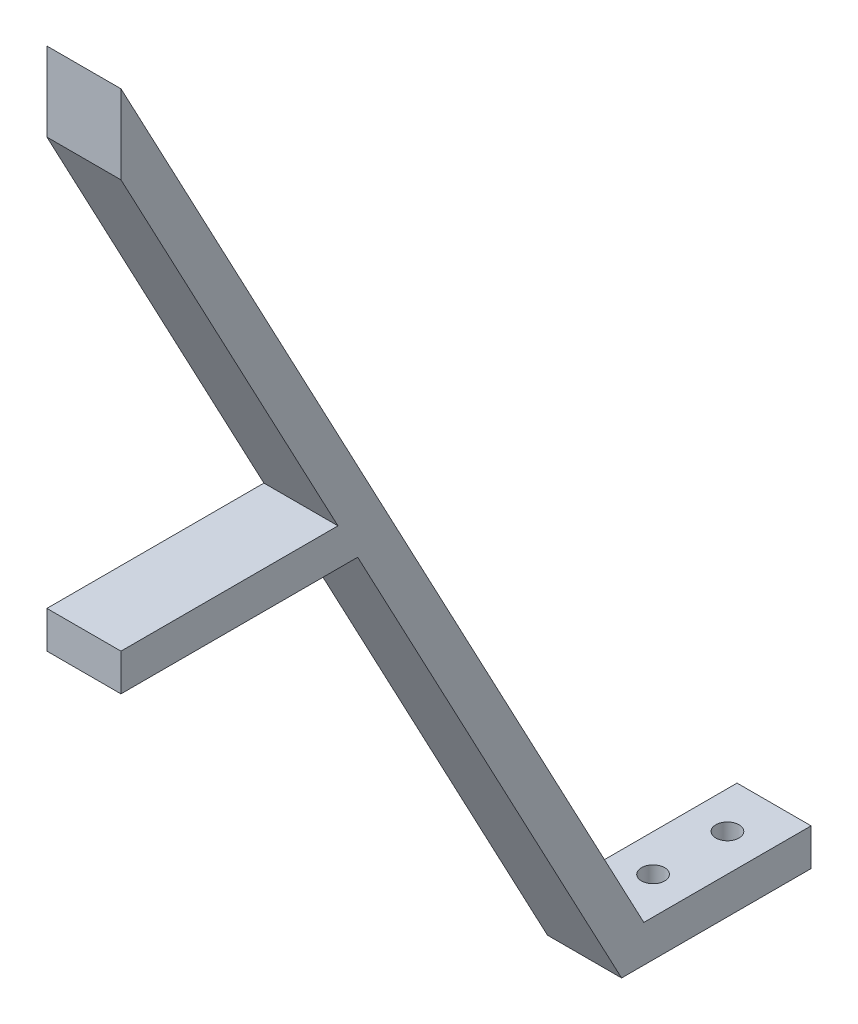
SolidWorks part; units mm, degrees
ref_plane "Alzado" through (0, 0, 0) normal (0, 0, 1) x (1, 0, 0)
ref_plane "Planta" through (0, 0, 0) normal (0, 1, 0) x (1, 0, 0)
ref_plane "Vista lateral" through (0, 0, 0) normal (1, 0, 0) x (0, 0, -1)
sketch "Croquis2" plane through (0, 0, 0) normal (1, 0, 0) x (0, 0, -1)
  line L0 (1.6204, -200.3696) -> (1.6204, 499.6304) construction
  line L1 (1.6204, 499.6304) -> (360.3116, -174.9696)
  line L2 (345.0497, -200.3696) -> (475.0497, -200.3696)
  line L3 (1.6204, 445.527) -> (150.499, 165.527)
  line L4 (1.6204, 499.6304) -> (289.9582, -42.6542) construction
  line L5 (-20.8065, 487.7058) -> (247.6855, -17.2542) construction
  line L6 (475.0497, -200.3696) -> (475.0497, -174.9696)
  line L7 (1.6204, 499.6304) -> (1.6204, 445.527)
  line L8 (1.6204, 165.527) -> (150.499, 165.527)
  line L9 (1.6204, 140.127) -> (164.0045, 140.127)
  line L10 (1.6204, 140.127) -> (1.6204, 165.527)
  line L11 (164.0045, 140.127) -> (345.0497, -200.3696)
  line L12 (0, -17.2542) -> (247.6855, -17.2542) construction
  line L13 (0, -42.6542) -> (289.9582, -42.6542) construction
  line L14 (1.6204, -200.3696) -> (345.0497, -200.3696) construction
  line L15 (475.0497, -174.9696) -> (360.3116, -174.9696)
  dimension "D1" = 25.4
  dimension "D2" = 28
  dimension "D4" = 280
  dimension "D5" = 25.4
  dimension "D6" = 130
  dimension "D7" = 700
  dimension "D3" = 25.4
extrude "Saliente-Extruir1" add sketch "Croquis2" along normal blind 50.8
sketch "Croquis3" plane through (0, -174.9696, 0) normal (0, 1, 0) x (1, 0, 0)
  line L0 (25.4, 475.0497) -> (25.4, 443.0497) construction
  line L1 (50.8, 475.0497) -> (0, 475.0497) construction
  line L2 (25.4, 443.0497) -> (25.4, 392.0497) construction
  circle A0 centre (25.4, 443.0497) radius 7.9375
  circle A1 centre (25.4, 392.0497) radius 7.9375
  dimension "D1" = 15.875
  dimension "D2" = 15.875
  dimension "D3" = 32
  dimension "D4" = 51
extrude "Cortar-Extruir1" cut sketch "Croquis3" against normal blind 50.8
